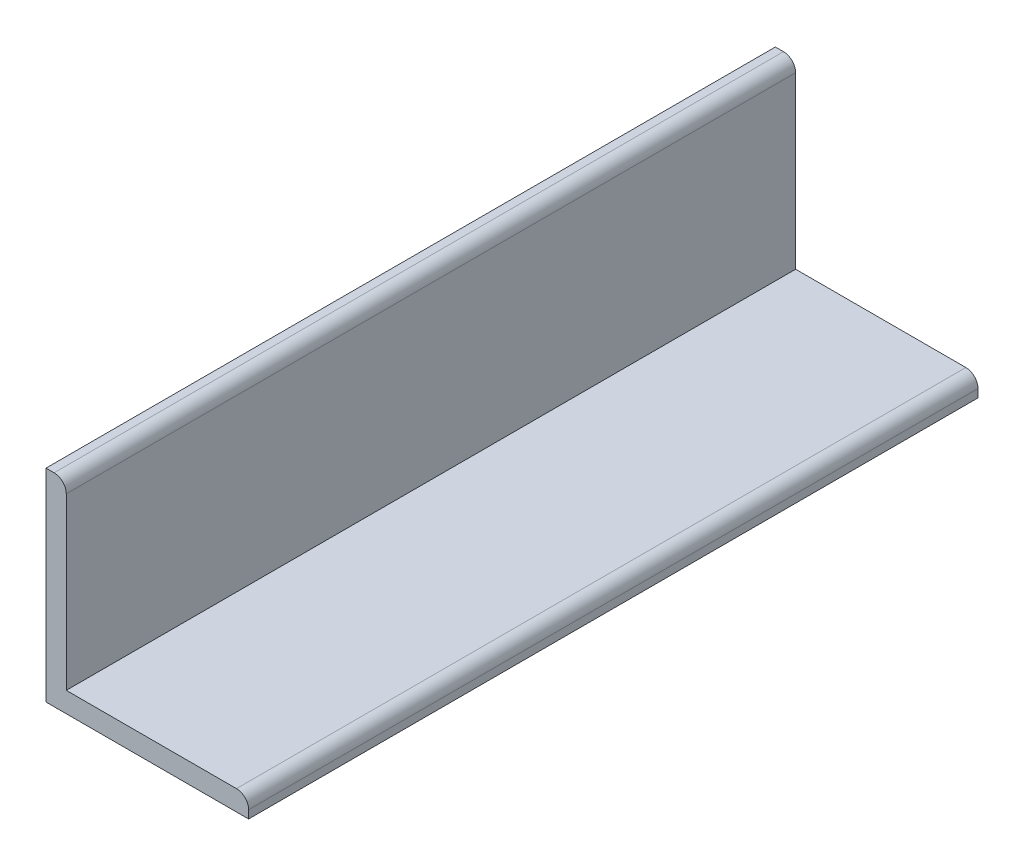
SolidWorks part; units mm, degrees
material "ASTM A36 Steel"
ref_plane "Front Plane" through (0, 0, 0) normal (0, 0, 1) x (1, 0, 0)
ref_plane "Top Plane" through (0, 0, 0) normal (0, 1, 0) x (1, 0, 0)
ref_plane "Right Plane" through (0, 0, 0) normal (1, 0, 0) x (0, 0, -1)
sketch "Sketch1" plane through (0, 0, 0) normal (0, 0, 1) x (1, 0, 0)
  line L0 (-20, 22) -> (-20, -20)
  line L1 (-25, -25) -> (25, -25)
  line L2 (-25, -25) -> (-25, 25)
  line L3 (-25, 25) -> (-23, 25)
  line L4 (25, -25) -> (25, -23)
  line L5 (-25, -25) -> (25, 25) construction
  line L6 (-25, 25) -> (25, -25) construction
  line L7 (-20, -20) -> (22, -20)
  arc A0 (22, -20) -> (25, -23) centre (22, -23) cw
  arc A1 (-20, 22) -> (-23, 25) centre (-23, 22) ccw
  point P0 (0, 0)
  dimension "D4" = 3
  dimension "D1" = 50
  dimension "D2" = 50
  dimension "D3" = 5
extrude "Boss-Extrude1" add sketch "Sketch1" along normal mid plane 180
